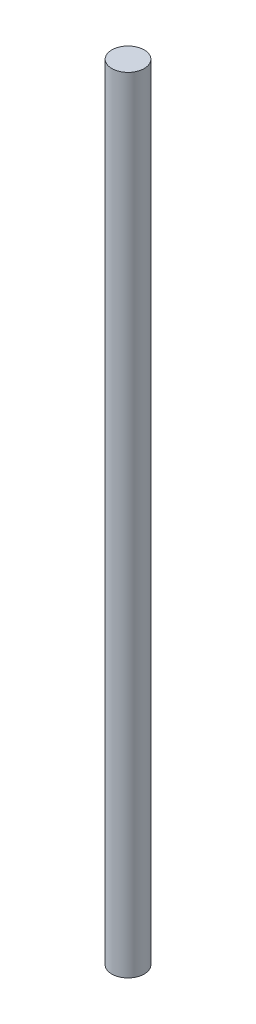
SolidWorks part; units mm, degrees
ref_plane "Front Plane" through (0, 0, 0) normal (0, 0, 1) x (1, 0, 0)
ref_plane "Top Plane" through (0, 0, 0) normal (0, 1, 0) x (1, 0, 0)
ref_plane "Right Plane" through (0, 0, 0) normal (1, 0, 0) x (0, 0, -1)
sketch "Sketch1" plane through (0, 0, 0) normal (0, 1, 0) x (1, 0, 0)
  circle A0 centre (0, 0) radius 2
  dimension "D1" = 4
extrude "Boss-Extrude1" add sketch "Sketch1" along normal blind 97
